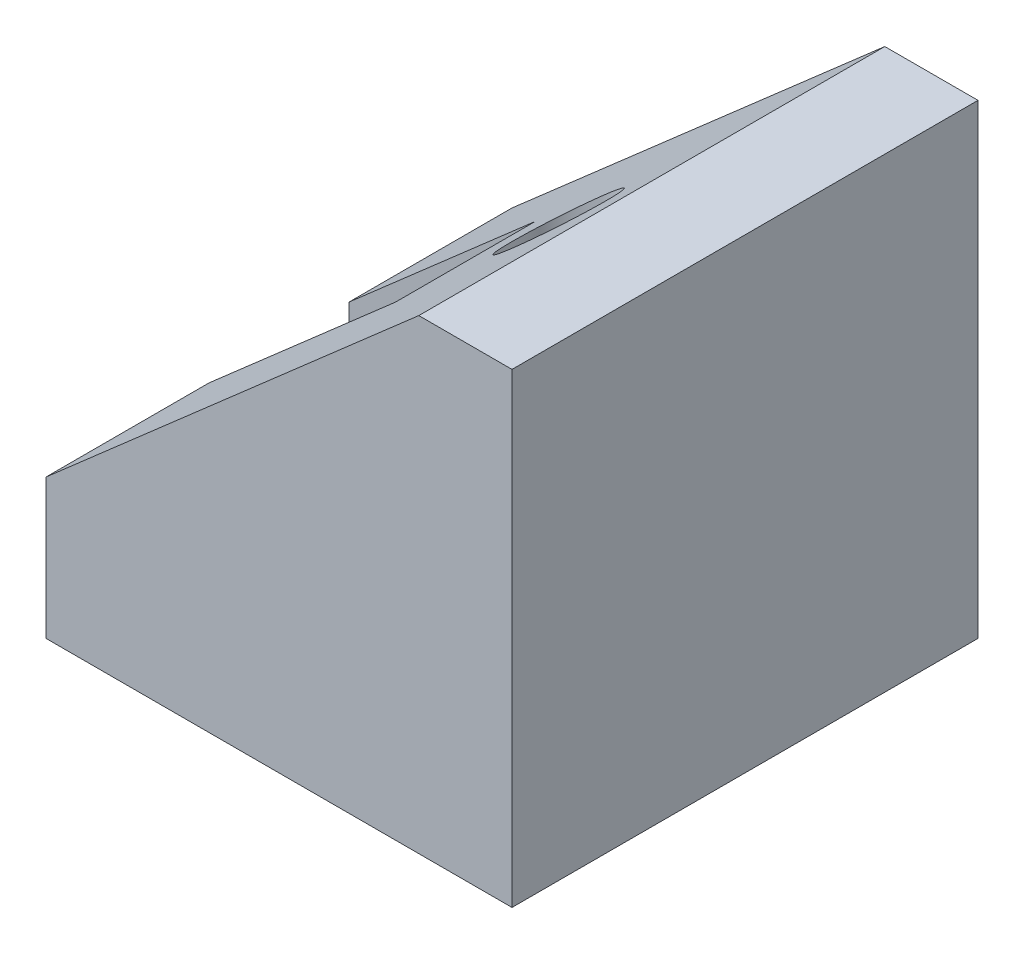
SolidWorks part; units mm, degrees
material "연성 주철"
ref_plane "Front Plane" through (0, 0, 0) normal (0, 0, 1) x (1, 0, 0)
ref_plane "Top Plane" through (0, 0, 0) normal (0, 1, 0) x (1, 0, 0)
ref_plane "Right Plane" through (0, 0, 0) normal (1, 0, 0) x (0, 0, -1)
sketch "Sketch1" plane through (0, 0, 0) normal (0, 0, 1) x (1, 0, 0)
  line L0 (0, 0) -> (0, 15)
  line L1 (0, 0) -> (50, 0)
  line L2 (50, 0) -> (50, 50)
  line L3 (50, 50) -> (40, 50)
  line L4 (40, 50) -> (0, 15)
  dimension "D1" = 15
  dimension "D2" = 50
  dimension "D3" = 50
  dimension "D4" = 10
extrude "Boss-Extrude1" add sketch "Sketch1" along normal blind 50
sketch "Sketch9" plane through (0, 0, 0) normal (0, -1, 0) x (-1, 0, 0)
  line L0 (0, -50) -> (0, 0) construction
  line L1 (0, 0) -> (-50, 0) construction
  circle A0 centre (-30, -25) radius 5
  dimension "D2" = 10
  dimension "D1" = 30
  dimension "D3" = 25
extrude "Cut-Extrude1" cut sketch "Sketch9" against normal through all contours A0
ref_plane "Plane4" through (0, 0, 0) normal (0, -1, 0) x (-1, 0, 0)
sketch "Sketch12" plane through (0, 0, 0) normal (0, -1, 0) x (-1, 0, 0)
  line L0 (0, -32.5) -> (-20, -32.5)
  line L1 (0, -50) -> (0, 0) construction
  line L2 (-20, -32.5) -> (-20, -17.5)
  line L3 (-20, -17.5) -> (0, -17.5)
  line L4 (0, -17.5) -> (0, -32.5)
  dimension "D1" = 15
  dimension "D2" = 17.5
  dimension "D3" = 20
extrude "Cut-Extrude3" cut sketch "Sketch12" against normal through all contours L0 L2 L3 L4
